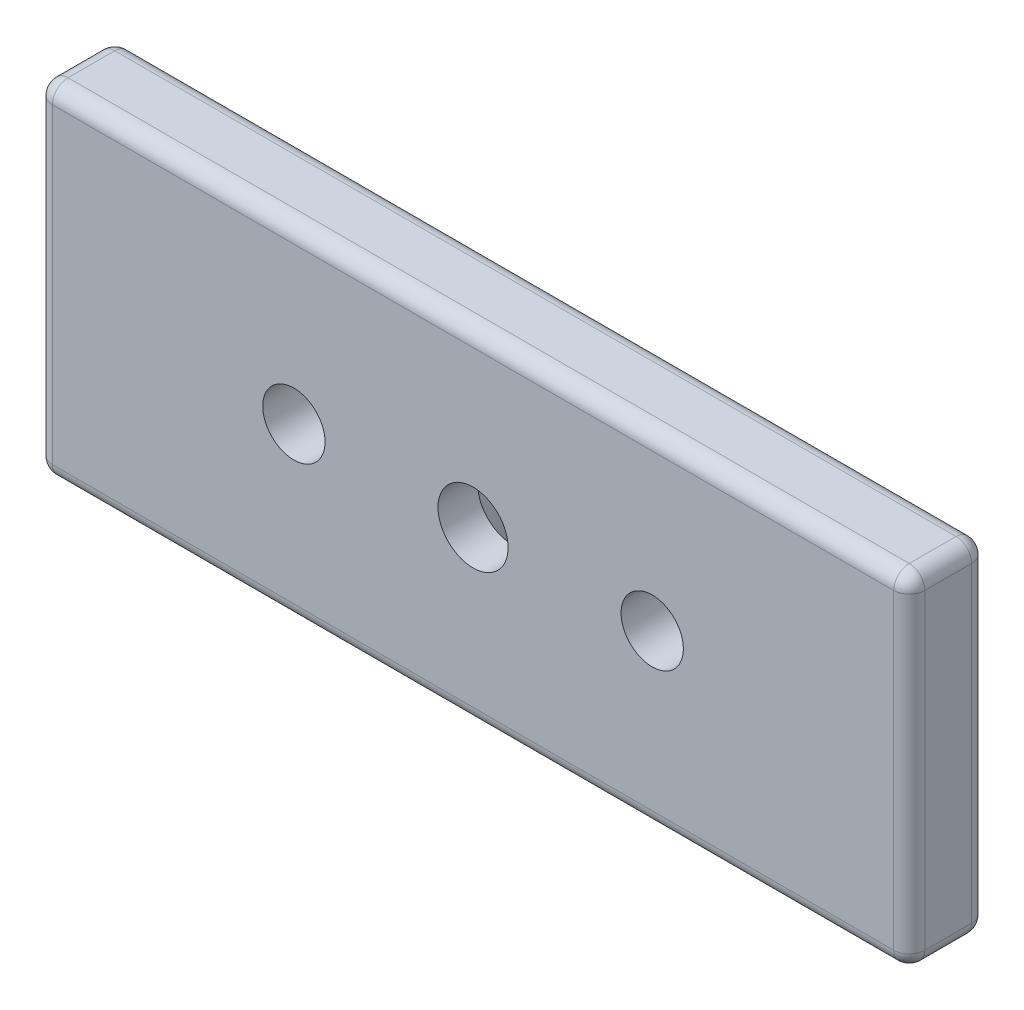
SolidWorks part; units mm, degrees
ref_plane "Front Plane" through (0, 0, 0) normal (0, 0, 1) x (1, 0, 0)
ref_plane "Top Plane" through (0, 0, 0) normal (0, 1, 0) x (1, 0, 0)
ref_plane "Right Plane" through (0, 0, 0) normal (1, 0, 0) x (0, 0, -1)
sketch "Sketch2" plane through (0, 0, 0) normal (0, 0, 1) x (1, 0, 0)
  line L1 (0, 0) -> (56, 0)
  line L2 (0, 0) -> (0, 22)
  line L3 (0, 22) -> (56, 22)
  line L4 (56, 0) -> (56, 22)
  dimension "D1" = 56
  dimension "D2" = 22
extrude "Boss-Extrude2" add sketch "Sketch2" against normal blind 5
sketch "Sketch5" plane through (0, 0, 0) normal (0, 0, 1) x (1, 0, 0)
  line L0 (0, 0) -> (56, 0) construction
  line L1 (0, 22) -> (0, 0) construction
  circle A0 centre (16.5, 11) radius 2
  circle A1 centre (39.5, 11) radius 2
  point P2 (0, 0)
  point P3 (0, 0)
  point P6 (44.268, 11)
  dimension "D1" = 4
  dimension "D2" = 11
  dimension "D3" = 16.5
  dimension "D4" = 39.5
extrude "Mounting Holes" cut sketch "Sketch5" against normal through all
fillet "Small Edge Fillet" radius 1 4 edges at (0, 0, -2.5) (56, 0, -2.5) (56, 22, -2.5) (0, 22, -2.5)
fillet "Front-Back Edge Fillet" radius 1 16 edges at (55.7071, 21.7071, -5) (56, 11, -5) (55.7071, 0.2929, -5) (0.2929, 0.2929, -5) (0, 11, -5) (0.2929, 21.7071, -5) (55.7071, 21.7071, 0) (56, 11, 0) (55.7071, 0.2929, 0) (0.2929, 0.2929, 0) (0, 11, 0) (0.2929, 21.7071, 0) (28, 0, -5) (28, 0, 0) (28, 22, -5) (28, 22, 0)
hole_wizard "CSK for M4 Flat Head Machine Screw2" positions "Sketch9" profile "Sketch10" countersink size "M4" standard "ANSI Metric" end condition through all
sketch "Sketch9" plane through (0, 0, -5) normal (0, 0, -1) x (-1, 0, 0)
  point P0 (-28, 11)
  point P2 (-28, 11)
  point P4 (-28, 11)
  point P6 (-28, 11)
  point P8 (-28, 11)
  point P10 (-28, 11)
sketch "Sketch10" plane through (28, 11, -5) normal (1, 0, 0) x (0, 1, 0)
  line L0 (0, 0) -> (0, 5)
  line L1 (0, 5) -> (2.25, 5)
  line L2 (2.25, 5) -> (2.25, 2.45)
  line L3 (2.25, 2.45) -> (4.7, 0)
  line L5 (4.7, 0) -> (0, 0)
  line L6 (-2.25, 2.45) -> (-4.7, 0) construction
  line L11 (0, -6.35) -> (0, 107.95) construction
  dimension "Thru Hole Dia." = 4.5
  dimension "Thru Hole Depth" = 5
  dimension "Near C'Sink Dia." = 9.4
  dimension "Near C'Sink Angle" = 90
